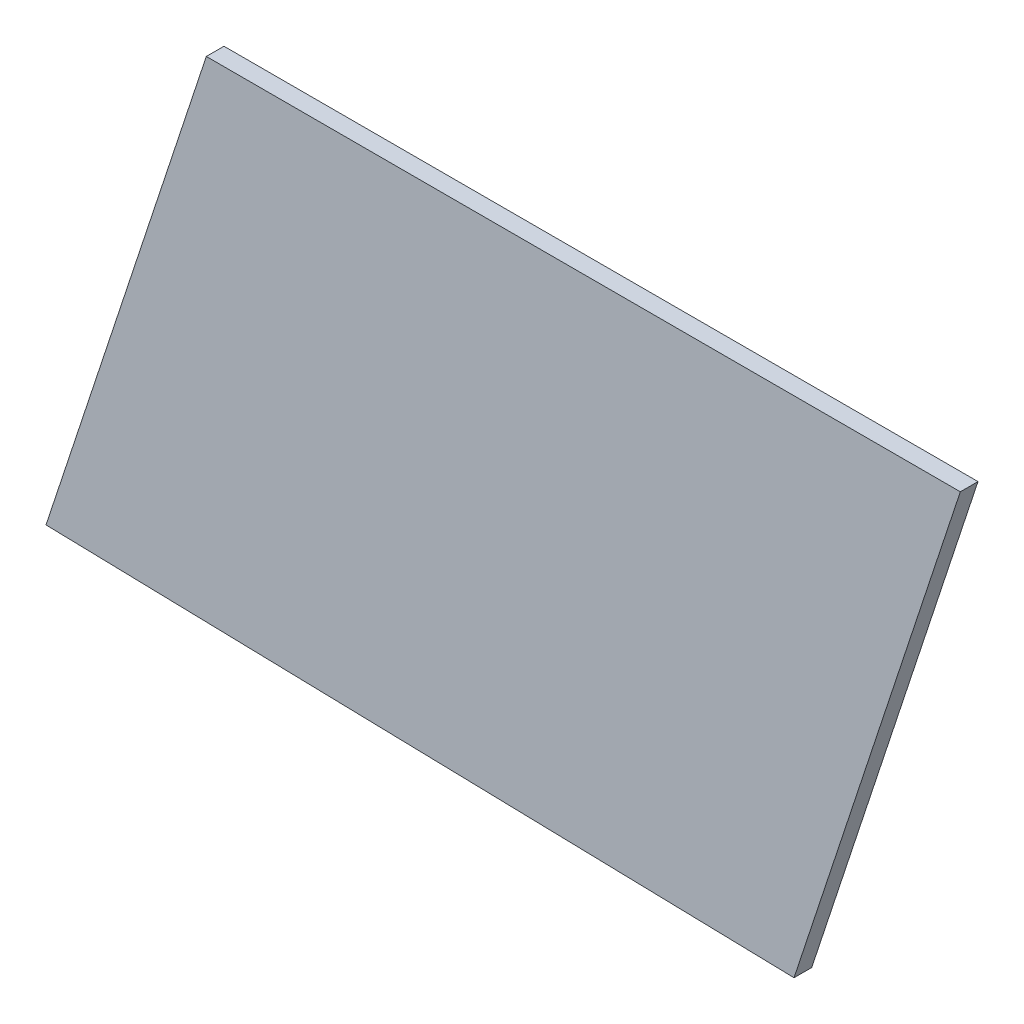
SolidWorks part; units mm, degrees
ref_plane "Front Plane" through (0, 0, 0) normal (0, 0, 1) x (1, 0, 0)
ref_plane "Top Plane" through (0, 0, 0) normal (0, 1, 0) x (1, 0, 0)
ref_plane "Right Plane" through (0, 0, 0) normal (1, 0, 0) x (0, 0, -1)
sketch "Sketch2" plane through (0, 0, 0) normal (0, 0, 1) x (1, 0, 0)
  line L0 (-54.6192, -24.5892) -> (30.7248, -24.5892)
  line L1 (-54.6192, -24.5892) -> (-71.4913, -75.7257)
  line L2 (30.7248, -24.5892) -> (13.8527, -75.7257)
  line L3 (-71.4913, -75.7257) -> (13.8527, -75.7257)
  dimension "D1" = 85.344
  dimension "D2" = 53.848
  dimension "D3" = 108.26
extrude "Boss-Extrude1" add sketch "Sketch2" along normal blind 2
sketch "Sketch3" plane through (0, 0, 2) normal (0, 0, 1) x (1, 0, 0)
  line L0 (-72.7647, -79.585) -> (11.9014, -81.6395)
  line L2 (-71.4913, -75.7257) -> (-72.7647, -79.585)
  line L3 (-72.7647, -79.585) -> (18.6346, -79.585) construction
  line L4 (-54.6192, -24.5892) -> (-71.4913, -75.7257) construction
  line L5 (13.8527, -75.7257) -> (11.9014, -81.6395)
  line L6 (13.8527, -75.7257) -> (30.7248, -24.5892) construction
  line L7 (-71.4913, -75.7257) -> (13.8527, -75.7257)
  dimension "D1" = 1.39
  dimension "D2" = 180
  dimension "D3" = 180
  dimension "D4" = 4.064
extrude "Boss-Extrude2" add sketch "Sketch3" against normal blind 2
